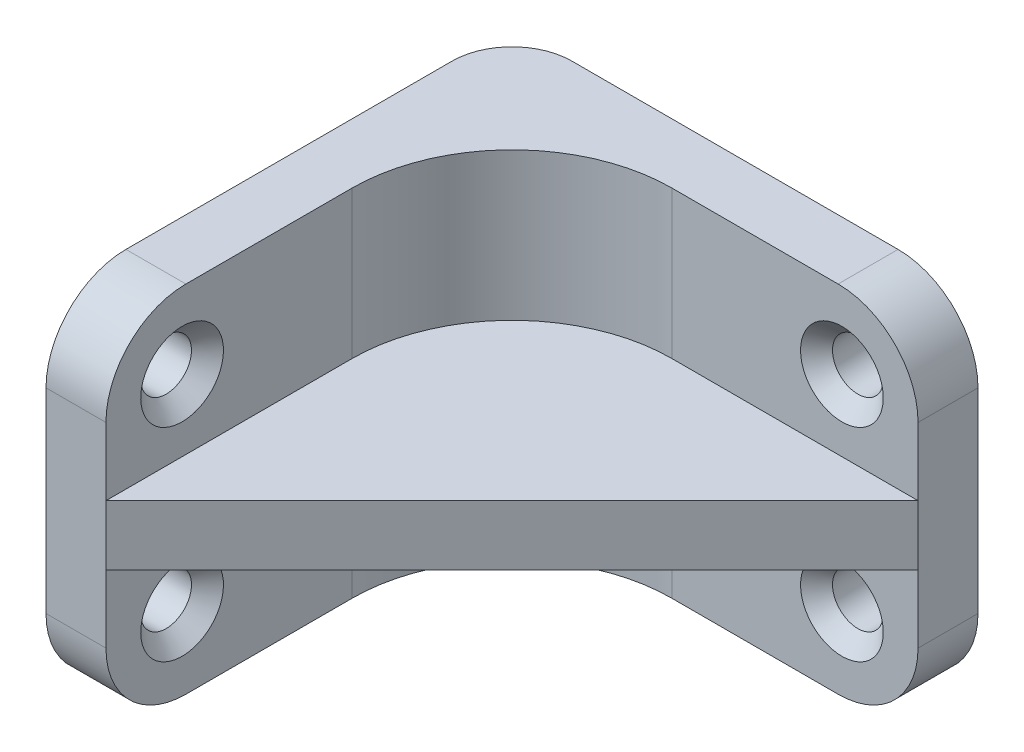
SolidWorks part; units mm, degrees
ref_plane "Front Plane" through (0, 0, 0) normal (0, 0, 1) x (1, 0, 0)
ref_plane "Top Plane" through (0, 0, 0) normal (0, 1, 0) x (1, 0, 0)
ref_plane "Right Plane" through (0, 0, 0) normal (1, 0, 0) x (0, 0, -1)
sketch "Sketch1" plane through (0, 0, 0) normal (0, 0, 1) x (1, 0, 0)
  line L0 (-0.1217, -12.7) -> (-50000.1217, -12.7) construction
  line L1 (-41.275, 9.525) -> (-0.475, 9.525)
  line L2 (9.525, 9.525) -> (-41.275, 9.525) construction
  line L3 (9.525, 9.525) -> (9.525, -34.925) construction
  line L4 (9.525, -34.925) -> (-41.275, -34.925) construction
  line L5 (-41.275, 9.525) -> (-41.275, -34.925)
  line L6 (9.525, -0.475) -> (9.525, -24.925)
  line L7 (-0.475, -34.925) -> (-41.275, -34.925)
  circle A0 centre (0, 0) radius 3.175
  circle A1 centre (0, -25.4) radius 3.175
  arc A2 (9.525, -24.925) -> (-0.475, -34.925) centre (-0.475, -24.925) cw
  arc A3 (-0.475, 9.525) -> (9.525, -0.475) centre (-0.475, -0.475) cw
  point P11 (9.525, -12.7)
  dimension "D1" = 9.525
  dimension "1/4\"" = 6.35
  dimension "D5" = 10
  dimension "D2" = 25.4
  dimension "D3" = 9.525
  dimension "D4" = 50.8
extrude "Boss-Extrude1" add sketch "Sketch1" along normal blind 7.5
sketch "Sketch2" plane through (-41.275, 0, 0) normal (-1, 0, 0) x (0, 0, 1)
  line L0 (49.956, -12.7) -> (-49950.044, -12.7) construction
  line L1 (7.5, 9.525) -> (48.3, 9.525)
  line L2 (58.3, 9.525) -> (7.5, 9.525) construction
  line L3 (58.3, 9.525) -> (58.3, -34.925) construction
  line L4 (58.3, -34.925) -> (7.5, -34.925) construction
  line L5 (7.5, 9.525) -> (7.5, -34.925)
  line L6 (58.3, -0.475) -> (58.3, -24.925)
  line L7 (48.3, -34.925) -> (7.5, -34.925)
  line L8 (7.5, 9.525) -> (7.5, -34.925) construction
  line L9 (7.5, -34.925) -> (0, -34.925) construction
  circle A0 centre (48.775, 0) radius 3.175
  circle A1 centre (48.775, -25.4) radius 3.175
  arc A2 (58.3, -24.925) -> (48.3, -34.925) centre (48.3, -24.925) cw
  arc A3 (48.3, 9.525) -> (58.3, -0.475) centre (48.3, -0.475) cw
  point P10 (30.4635, -28.1683)
  point P17 (0, 0)
  point P18 (0, 0)
  point P19 (0, 0)
  point P20 (7.5, 9.525)
  point P23 (7.5, -12.7)
  point P24 (48.3, -21.8119)
  dimension "D1" = 6.35
  dimension "D2" = 6.35
  dimension "D4" = 10
  dimension "D5" = 10
  dimension "D3" = 44.45
  dimension "D6" = 40.8
  dimension "D7" = 12.7
  dimension "D8" = 12.7
  dimension "D9" = 9.525
extrude "Boss-Extrude2" add sketch "Sketch2" along normal blind 7.5 separate body
sketch "Sketch3" plane through (0, -34.925, 0) normal (0, -1, 0) x (1, 0, 0)
  line L0 (-48.775, 7.5) -> (-41.275, 7.5) construction
  line L1 (-41.275, 7.5) -> (-41.275, 0) construction
  line L2 (-48.775, 7.5) -> (-41.275, 7.5)
  line L3 (-41.275, 7.5) -> (-41.275, 0)
  arc A0 (-48.775, 7.5) -> (-41.275, 0) centre (-41.275, 7.5) ccw
  point P4 (0, 0)
extrude "Boss-Extrude3" add sketch "Sketch3" against normal up to surface (44.45 mm away) up to face at (-45.025, 9.525, 27.9)
fillet "Fillet1" radius 20 1 edges at (-41.275, -12.7, 7.5)
ref_plane "Plane1" through (0, -12.7, 0) normal (0, 1, 0) x (1, 0, 0)
sketch "Sketch4" plane through (0, -12.7, 0) normal (0, 1, 0) x (1, 0, 0)
  line L0 (-41.275, -51.95) -> (-41.275, -45.6) construction
  line L1 (-3.175, -7.5) -> (3.175, -7.5) construction
  line L2 (-41.275, -51.95) -> (-41.275, -45.6) construction
  line L3 (-3.175, -7.5) -> (3.175, -7.5) construction
  line L4 (-0.475, -7.5) -> (9.525, -7.5) construction
  line L5 (-21.275, -7.5) -> (-0.475, -7.5) construction
  line L6 (-41.275, -27.5) -> (-41.275, -48.3) construction
  line L7 (-41.275, -58.3) -> (-41.275, -48.3) construction
  line L8 (-0.475, -7.5) -> (9.525, -7.5)
  line L9 (-21.275, -7.5) -> (-0.475, -7.5)
  line L10 (-41.275, -27.5) -> (-41.275, -48.3)
  line L11 (-41.275, -58.3) -> (-41.275, -48.3)
  line L12 (-41.275, -58.3) -> (9.525, -7.5)
  arc A0 (-21.275, -7.5) -> (-41.275, -27.5) centre (-21.275, -27.5) ccw construction
  arc A1 (-21.275, -7.5) -> (-41.275, -27.5) centre (-21.275, -27.5) ccw
extrude "Boss-Extrude4" add sketch "Sketch4" along normal mid plane 7.5
chamfer "Chamfer1" distance 2 angle 45 4 edges at (-3.175, -25.4, 7.5) (3.175, 0, 7.5) (-41.275, -3.175, 48.775) (-41.275, -22.225, 48.775)
